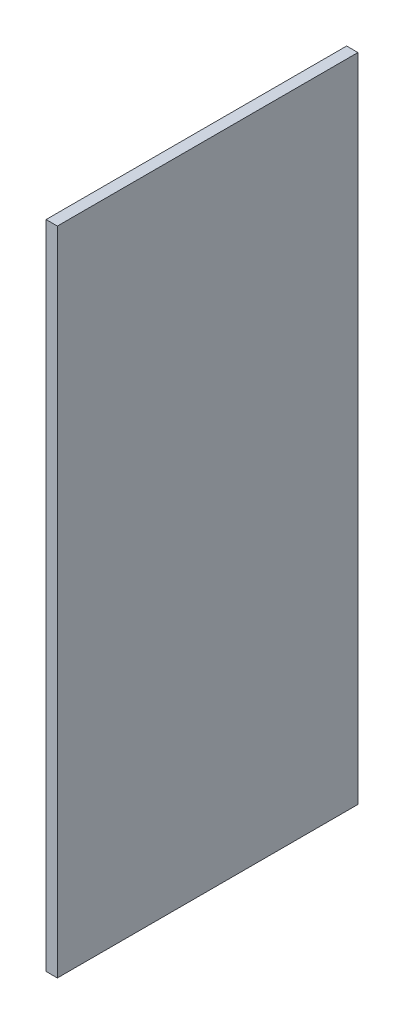
SolidWorks part; units mm, degrees
ref_plane "Front Plane" through (0, 0, 0) normal (0, 0, 1) x (1, 0, 0)
ref_plane "Top Plane" through (0, 0, 0) normal (0, 1, 0) x (1, 0, 0)
ref_plane "Right Plane" through (0, 0, 0) normal (1, 0, 0) x (0, 0, -1)
other "Configuration Table"
sketch "Sketch1" plane through (0, 0, 0) normal (0, 0, 1) x (1, 0, 0)
  line L1 (1.5, 120) -> (31.5, 120)
  line L2 (1.5, 120) -> (1.5, 1850)
  line L3 (1.5, 1850) -> (31.5, 1850)
  line L4 (31.5, 120) -> (31.5, 1850)
extrude "OVEN_yalitim_tasyunu_sol_1" add sketch "Sketch1" against normal blind 798.5 from offset 20 separate body
